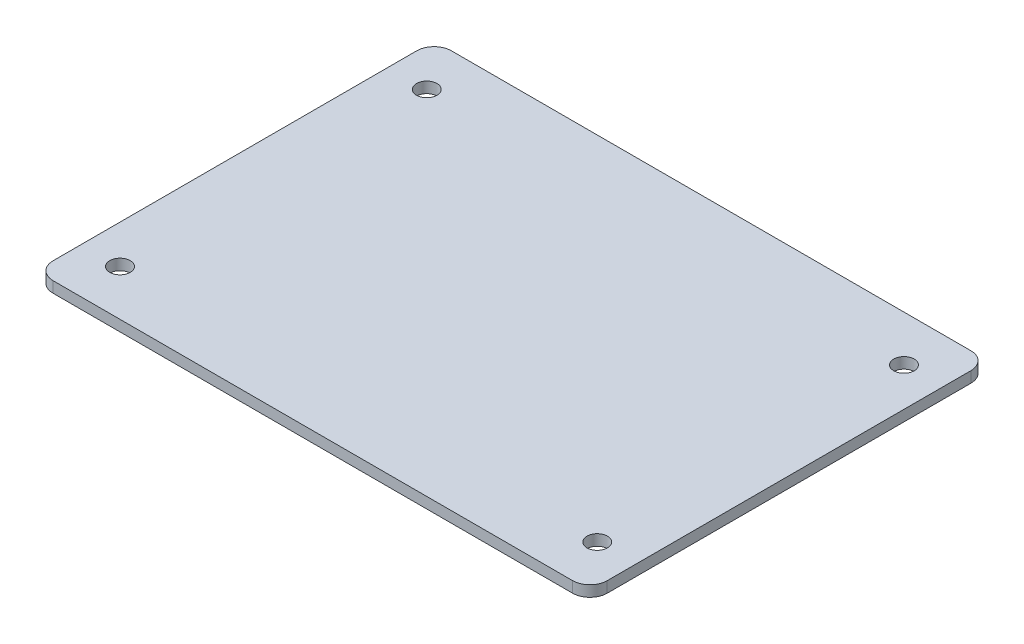
SolidWorks part; units mm, degrees
ref_plane "Спереди" through (0, 0, 0) normal (0, 0, 1) x (1, 0, 0)
ref_plane "Сверху" through (0, 0, 0) normal (0, 1, 0) x (1, 0, 0)
ref_plane "Справа" through (0, 0, 0) normal (1, 0, 0) x (0, 0, -1)
sketch "Эскиз1" plane through (0, 0, 0) normal (0, 1, 0) x (1, 0, 0)
  line L0 (0, 33.4777) -> (0, -33.2662) construction
  line L5 (38.1, -29.21) -> (-38.1, -29.21)
  line L6 (40.64, -26.67) -> (40.64, 26.67)
  line L7 (38.1, 29.21) -> (-38.1, 29.21)
  line L8 (-40.64, -26.67) -> (-40.64, 26.67)
  line L9 (40.64, -29.21) -> (-40.64, 29.21) construction
  line L10 (40.64, 29.21) -> (-40.64, -29.21) construction
  line L11 (-44.4178, 0) -> (45.3376, 0) construction
  arc A0 (40.64, 26.67) -> (38.1, 29.21) centre (38.1, 26.67) ccw
  arc A1 (38.1, -29.21) -> (40.64, -26.67) centre (38.1, -26.67) ccw
  arc A2 (-38.1, -29.21) -> (-40.64, -26.67) centre (-38.1, -26.67) cw
  arc A3 (-38.1, 29.21) -> (-40.64, 26.67) centre (-38.1, 26.67) ccw
  circle A4 centre (-35, 22.5) radius 1.5
  circle A5 centre (35, 22.5) radius 1.5
  circle A6 centre (35, -22.5) radius 1.5
  circle A7 centre (-35, -22.5) radius 1.5
  point P0 (0, 0)
  point P31 (0, 0)
  point P32 (0, 0)
  dimension "D3" = 2.54
  dimension "D4" = 3
  dimension "D1" = 81.28
  dimension "D2" = 58.42
  dimension "D5" = 70
  dimension "D6" = 45
extrude "Бобышка-Вытянуть1" add sketch "Эскиз1" along normal blind 1.6
